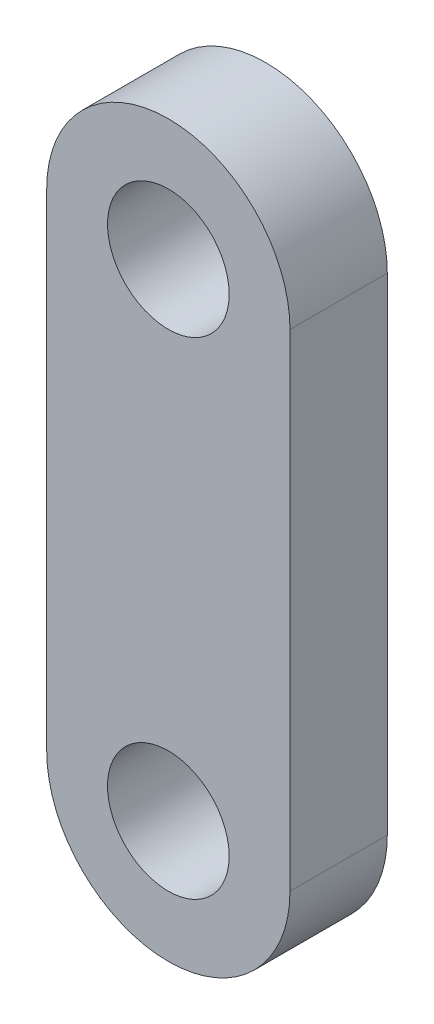
SolidWorks part; units mm, degrees
material "Stainless Steel (ferritic)"
ref_plane "Front Plane" through (0, 0, 0) normal (0, 0, 1) x (1, 0, 0)
ref_plane "Top Plane" through (0, 0, 0) normal (0, 1, 0) x (1, 0, 0)
ref_plane "Right Plane" through (0, 0, 0) normal (1, 0, 0) x (0, 0, -1)
sketch "Sketch1" plane through (0, 0, 0) normal (0, 0, 1) x (1, 0, 0)
  line L2 (10, 0) -> (10, 40)
  line L3 (-10, 0) -> (-10, 40)
  arc A5 (-10, 0) -> (10, 0) centre (0, 0) ccw
  arc A6 (10, 40) -> (-10, 40) centre (0, 40) ccw
  circle A7 centre (0, 40) radius 5
  circle A8 centre (0, 0) radius 5
  dimension "D1" = 20
  dimension "D4" = 10
  dimension "D5" = 10
  dimension "D3" = 20
  dimension "D2" = 40
extrude "Boss-Extrude1" add sketch "Sketch1" against normal blind 8 contours A7 | A8 | A6 L3 A5 L2
cosmetic thread "Cosmetic Thread1" parameters "D2"=11
cosmetic thread "Cosmetic Thread2" parameters "D2"=11
